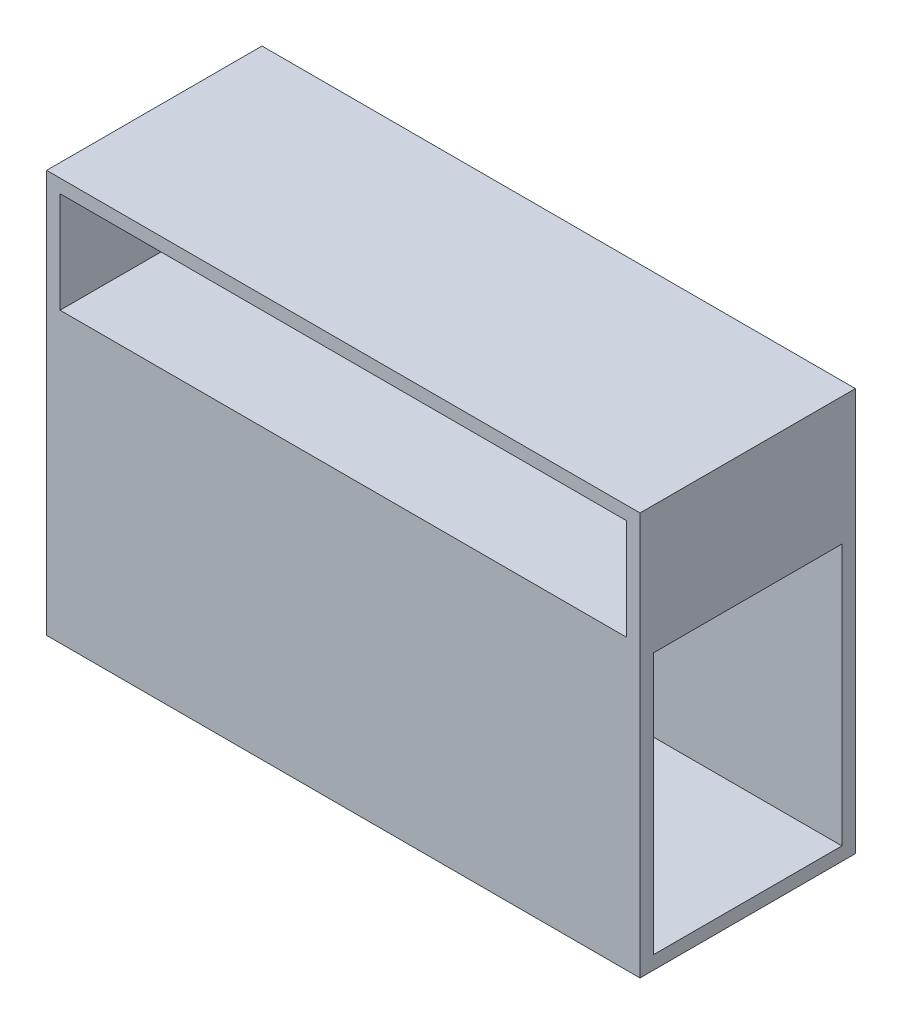
SolidWorks part; units mm, degrees
ref_plane "Front Plane" through (0, 0, 0) normal (0, 0, 1) x (1, 0, 0)
ref_plane "Top Plane" through (0, 0, 0) normal (0, 1, 0) x (1, 0, 0)
ref_plane "Right Plane" through (0, 0, 0) normal (1, 0, 0) x (0, 0, -1)
sketch "Sketch1" plane through (0, 0, 0) normal (0, 0, 1) x (1, 0, 0)
  line L1 (-44.0842, -29.9214) -> (44.0842, -29.9214)
  line L2 (-44.0842, -29.9214) -> (-44.0842, 29.9214)
  line L3 (-44.0842, 29.9214) -> (44.0842, 29.9214)
  line L4 (44.0842, -29.9214) -> (44.0842, 29.9214)
  line L5 (-44.0842, -29.9214) -> (44.0842, 29.9214) construction
  line L6 (-44.0842, 29.9214) -> (44.0842, -29.9214) construction
  point P0 (0, 0)
extrude "Boss-Extrude4" add sketch "Sketch1" along normal blind 2
sketch "Sketch2" plane through (0, 0, 2) normal (0, 0, 1) x (1, 0, 0)
  line L0 (-44.0842, -29.9214) -> (44.0842, -29.9214) construction
  line L1 (-44.0842, 29.9214) -> (-42.0842, 29.9214)
  line L2 (-44.0842, 29.9214) -> (-44.0842, -29.9214)
  line L3 (-44.0842, -29.9214) -> (-42.0842, -29.9214)
  line L4 (-42.0842, 29.9214) -> (-42.0842, -29.9214)
  line L6 (44.0842, 29.9214) -> (42.0842, 29.9214)
  line L7 (44.0842, 29.9214) -> (44.0842, -29.9214)
  line L8 (44.0842, -29.9214) -> (42.0842, -29.9214)
  line L9 (42.0842, 29.9214) -> (42.0842, -29.9214)
  dimension "D1" = 2
extrude "Boss-Extrude5" add sketch "Sketch2" along normal blind 30
sketch "Sketch3" plane through (0, 0, 2) normal (0, 0, 1) x (1, 0, 0)
  line L0 (-42.0842, -29.9214) -> (-42.0842, 29.9214) construction
  line L1 (-42.0842, 29.9214) -> (42.0842, 29.9214)
  line L2 (-42.0842, 29.9214) -> (-42.0842, 27.9214)
  line L3 (-42.0842, 27.9214) -> (42.0842, 27.9214)
  line L4 (42.0842, 29.9214) -> (42.0842, 27.9214)
  line L5 (42.0842, 29.9214) -> (42.0842, -29.9214) construction
  line L6 (42.0842, 29.9214) -> (-42.0842, 29.9214) construction
  line L7 (42.0842, -29.9214) -> (-42.0842, -29.9214)
  line L8 (42.0842, -29.9214) -> (42.0842, -27.9214)
  line L9 (42.0842, -27.9214) -> (-42.0842, -27.9214)
  line L10 (-42.0842, -29.9214) -> (-42.0842, -27.9214)
  line L11 (-42.0842, -29.9214) -> (-42.0842, 29.9214) construction
  line L12 (-42.0842, 12.9214) -> (42.0842, 12.9214)
  line L13 (-42.0842, 12.9214) -> (-42.0842, 10.9214)
  line L14 (-42.0842, 10.9214) -> (42.0842, 10.9214)
  line L15 (42.0842, 12.9214) -> (42.0842, 10.9214)
  dimension "D1" = 2
  dimension "D2" = 2
  dimension "D3" = 15
extrude "Boss-Extrude6" add sketch "Sketch3" along normal blind 30
sketch "Sketch4" plane through (-42.0842, 0, 0) normal (1, 0, 0) x (0, 0, -1)
  line L4 (-2, 10.9214) -> (-32, 10.9214)
  line L5 (-32, 10.9214) -> (-32, -27.9214)
  line L6 (-32, -27.9214) -> (-2, -27.9214)
  line L7 (-2, -27.9214) -> (-2, 10.9214)
  line L8 (-2, 10.9214) -> (-32, 10.9214)
  line L9 (-32, 10.9214) -> (-32, -27.9214)
  line L10 (-32, -27.9214) -> (-2, -27.9214)
  line L11 (-2, -27.9214) -> (-2, 10.9214)
  dimension "D1" = 0
extrude "Cut-Extrude1" cut sketch "Sketch4" against normal blind 30
sketch "Sketch5" plane through (42.0842, 0, 0) normal (-1, 0, 0) x (0, 0, 1)
  line L0 (32, -27.9214) -> (2, -27.9214) construction
  line L1 (32, 10.9214) -> (30, 10.9214)
  line L2 (32, 10.9214) -> (32, -27.9214)
  line L3 (32, -27.9214) -> (30, -27.9214)
  line L4 (30, 10.9214) -> (30, -27.9214)
  dimension "D1" = 2
extrude "Boss-Extrude7" add sketch "Sketch5" along normal up to surface (86.1684 mm away) up to face at (-44.0842, -4.25, 16.5)
sketch "Sketch6" plane through (42.0842, 0, 0) normal (-1, 0, 0) x (0, 0, 1)
  line L4 (30, -27.9214) -> (30, 10.9214)
  line L5 (30, 10.9214) -> (2, 10.9214)
  line L6 (2, 10.9214) -> (2, -27.9214)
  line L7 (2, -27.9214) -> (30, -27.9214)
  line L8 (30, -27.9214) -> (30, 10.9214)
  line L9 (30, 10.9214) -> (2, 10.9214)
  line L10 (2, 10.9214) -> (2, -27.9214)
  line L11 (2, -27.9214) -> (30, -27.9214)
  dimension "D1" = 0
extrude "Cut-Extrude2" cut sketch "Sketch6" against normal through all
